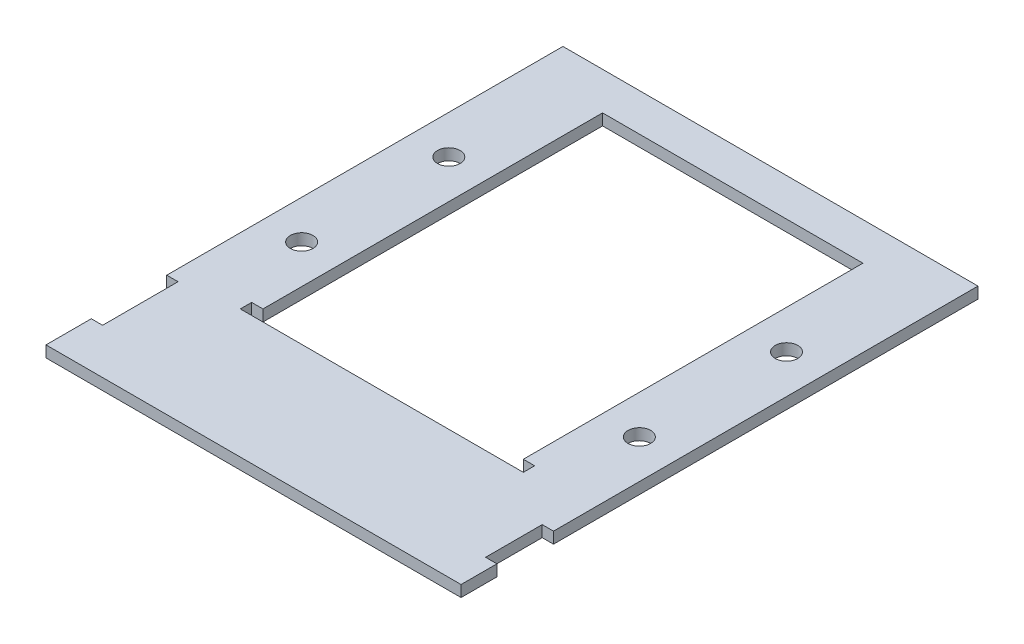
SolidWorks part; units mm, degrees
ref_plane "Alzado" through (0, 0, 0) normal (0, 0, 1) x (1, 0, 0)
ref_plane "Planta" through (0, 0, 0) normal (0, 1, 0) x (1, 0, 0)
ref_plane "Vista lateral" through (0, 0, 0) normal (1, 0, 0) x (0, 0, -1)
sketch "Croquis1" plane through (0, 0, 0) normal (0, 1, 0) x (1, 0, 0)
  line L1 (110, 3) -> (110, 12.5)
  line L2 (89.5, 37) -> (20.5, 37)
  line L3 (3, 20) -> (3, 15)
  line L4 (110, 27.5) -> (110, 37)
  line L5 (89.5, 40) -> (89.5, 130)
  line L6 (110, 3) -> (110, 12.5)
  line L7 (110, 140) -> (89.5, 140)
  line L9 (107, 12.5) -> (110, 12.5)
  line L10 (107, 27.5) -> (110, 27.5)
  line L11 (107, 20) -> (107, 12.5)
  line L12 (20.5, 140) -> (89.5, 140)
  line L13 (89.5, 130) -> (20.5, 130)
  line L14 (110, 27.5) -> (110, 140)
  line L15 (0, 50) -> (0, 35)
  line L17 (0, 15) -> (0, 3)
  line L18 (3, 35) -> (0, 35)
  line L19 (3, 15) -> (0, 15)
  line L20 (20.5, 37) -> (17.5, 37)
  line L21 (17.5, 37) -> (17.5, 40)
  line L22 (107, 20) -> (107, 27.5)
  line L23 (0, 140) -> (20.5, 140)
  line L24 (3, 20) -> (3, 35)
  line L25 (20.5, 40) -> (20.5, 130)
  line L26 (17.5, 40) -> (20.5, 40)
  line L28 (92.5, 40) -> (89.5, 40)
  line L29 (92.5, 37) -> (92.5, 40)
  line L30 (0, 50) -> (0, 140)
  line L31 (89.5, 37) -> (92.5, 37)
  line L32 (110, 3) -> (0, 3)
  circle A0 centre (99.75, 60.5) radius 3
  circle A1 centre (99.75, 99.5) radius 3
  circle A2 centre (10.25, 99.5) radius 3
  circle A3 centre (10.25, 60.5) radius 3
  point P33 (55, 130)
  point P34 (55, 140)
  dimension "D7" = 6
  dimension "D9" = 6
  dimension "D1" = 15
  dimension "D3" = 20.5
  dimension "D6" = 5
  dimension "D8" = 3
  dimension "D10" = 3
extrude "Saliente-Extruir1" add sketch "Croquis1" along normal blind 3
